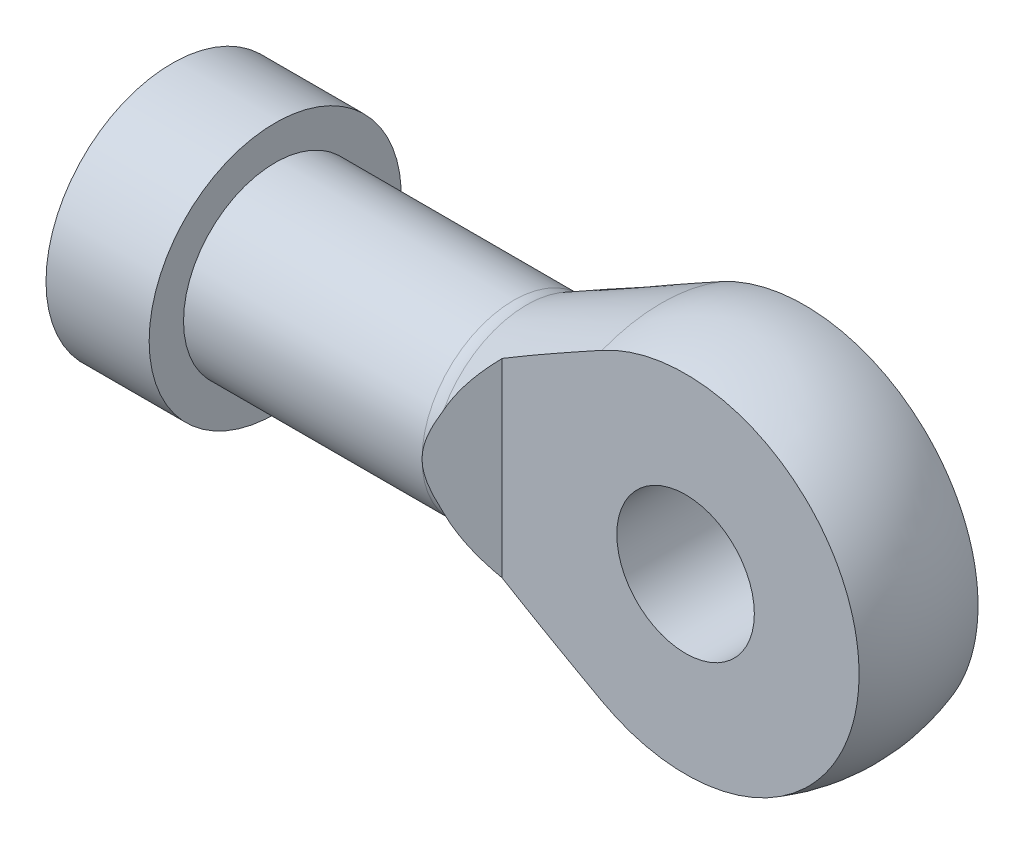
SolidWorks part; units mm, degrees
ref_plane "前视基准面" through (0, 0, 0) normal (0, 0, 1) x (1, 0, 0)
ref_plane "上视基准面" through (0, 0, 0) normal (0, 1, 0) x (1, 0, 0)
ref_plane "右视基准面" through (0, 0, 0) normal (1, 0, 0) x (0, 0, -1)
sketch "草图1" plane through (0, 0, 0) normal (0, 1, 0) x (1, 0, 0)
  line L0 (0, 0) -> (119.1734, 0) construction
  line L1 (0, 0) -> (0, 11)
  line L2 (0, 11) -> (9, 11)
  line L3 (9, 11) -> (9, 8)
  line L4 (9, 8) -> (29.8113, 8)
  line L5 (0, 0) -> (66, 0)
  line L6 (30.945, 8.2225) -> (42.7114, 14.2435)
  arc A1 (30.945, 8.2225) -> (29.8113, 8) centre (29.8113, 11) cw
  arc A2 (66, 0) -> (42.7114, 14.2435) centre (50, 0) ccw
  dimension "D6" = 3
  dimension "D1" = 11
  dimension "D2" = 8
  dimension "D3" = 9
  dimension "D5" = 50
revolve "旋转1" add sketch "草图1" angle 360 about L0
sketch "草图2" plane through (0, 0, 0) normal (0, 1, 0) x (1, 0, 0)
  line L0 (34, 5.1913) -> (29.8113, 8)
  line L1 (34, 5.1913) -> (73.5761, 5.1913)
  line L2 (29.8113, 0) -> (66, 0) construction
  line L3 (29.8113, -8) -> (29.8113, 8) construction
  line L4 (34, -5.1913) -> (29.8113, -8)
  line L5 (34, -5.1913) -> (73.5761, -5.1913)
  line L6 (72.2873, -20.4067) -> (73.5761, -5.1913)
  line L7 (29.8113, 8) -> (29.0098, 16.1508)
  line L8 (29.0098, 16.1508) -> (72.2873, 20.4067)
  line L9 (72.2873, 20.4067) -> (73.5761, 5.1913)
  line L10 (73.5761, 5.1913) -> (73.7255, 5.2569)
  line L11 (29.0098, -16.1508) -> (72.2873, -20.4067)
  line L13 (29.8113, -8) -> (29.0098, -16.1508)
  arc A1 (42.7114, -14.2435) -> (42.7114, 14.2435) centre (50, 0) ccw construction
  point P0 (53.788, -0.8087)
extrude "拉伸1" cut sketch "草图2" against normal mid plane 35 contours L9 L8 L7 L0 L1 | L4 L13 L11 L6 L5
sketch "草图3" plane through (0, 0, -5.1913) normal (0, 0, -1) x (-1, 0, 0)
  circle A0 centre (-50, 0) radius 6
  dimension "D1" = 12
extrude "拉伸2" cut sketch "草图3" against normal blind 30
sketch "草图4" plane through (0, 0, 0) normal (-1, 0, 0) x (0, 0, 1)
  circle A0 centre (0, 0) radius 6
  dimension "D1" = 12
extrude "拉伸3" cut sketch "草图4" against normal blind 30
